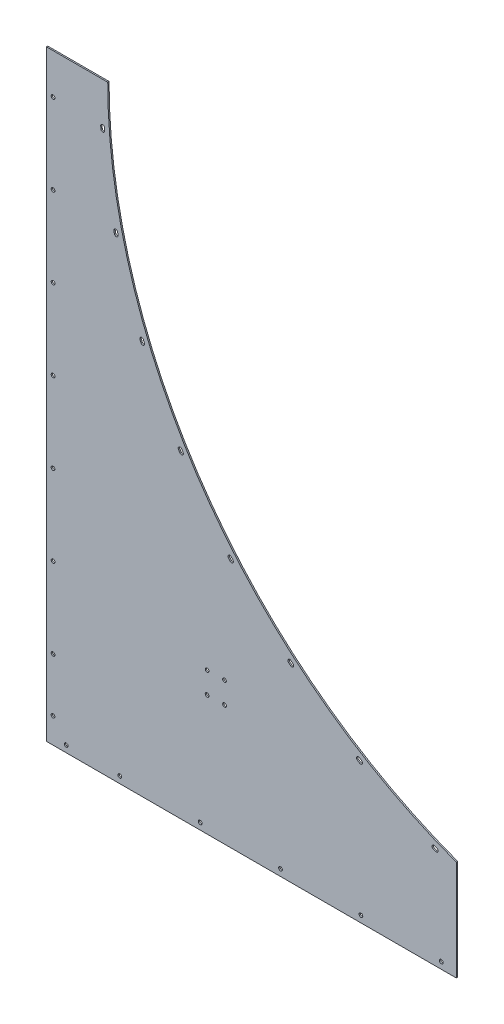
SolidWorks part; units mm, degrees
ref_plane "Front Plane" through (0, 0, 0) normal (0, 0, 1) x (1, 0, 0)
ref_plane "Top Plane" through (0, 0, 0) normal (0, 1, 0) x (1, 0, 0)
ref_plane "Right Plane" through (0, 0, 0) normal (1, 0, 0) x (0, 0, -1)
sketch "Sketch1" plane through (0, 0, 0) normal (0, 0, 1) x (1, 0, 0)
  line L0 (1502.6407, 642.1541) -> (1502.6407, 267.5522)
  line L1 (1502.6407, 267.5522) -> (-27.3593, 267.5522)
  line L2 (-27.3593, 267.5522) -> (-27.3593, 2512.5522)
  line L3 (-27.3593, 2512.5522) -> (201.6407, 2512.5522)
  line L4 (190.2384, 2349.6294) -> (189.4538, 2359.5986)
  line L5 (175.497, 2358.5002) -> (176.2816, 2348.531)
  line L6 (240.4273, 2037.7648) -> (238.0928, 2047.4885)
  line L7 (224.4796, 2044.2203) -> (226.8141, 2034.4966)
  line L8 (338.7846, 1737.591) -> (334.9578, 1746.8298)
  line L9 (322.0235, 1741.4723) -> (325.8503, 1732.2335)
  line L10 (482.8885, 1456.4994) -> (477.6636, 1465.0258)
  line L11 (465.7266, 1457.7108) -> (470.9516, 1449.1844)
  line L12 (669.1907, 1201.4112) -> (662.6962, 1209.0153)
  line L13 (652.0506, 1199.923) -> (658.545, 1192.3189)
  line L14 (893.1038, 978.6077) -> (885.4997, 985.1022)
  line L15 (876.4075, 974.4565) -> (884.0115, 967.962)
  line L16 (1149.1143, 793.575) -> (1140.5879, 798.8)
  line L17 (1133.2729, 786.863) -> (1141.7993, 781.6381)
  line L18 (1430.9183, 650.8693) -> (1421.6795, 654.6961)
  line L19 (1416.322, 641.7618) -> (1425.5608, 637.9349)
  arc A0 (201.6407, 2512.5522) -> (1502.6407, 642.1541) centre (2196.6407, 2512.5522) ccw
  circle A1 centre (1446.6407, 292.5522) radius 7
  circle A2 centre (1146.6407, 292.5522) radius 7
  circle A3 centre (846.6407, 292.5522) radius 7
  circle A4 centre (546.6407, 292.5522) radius 7
  circle A5 centre (246.6407, 292.5522) radius 7
  circle A6 centre (46.6407, 292.5522) radius 7
  circle A7 centre (-2.3593, 362.5522) radius 7
  circle A8 centre (-2.3593, 562.5522) radius 7
  circle A9 centre (-2.3593, 862.5522) radius 7
  circle A10 centre (-2.3593, 1162.5522) radius 7
  circle A11 centre (-2.3593, 1462.5522) radius 7
  circle A12 centre (-2.3593, 1762.5522) radius 7
  circle A13 centre (-2.3593, 2062.5522) radius 7
  circle A14 centre (-2.3593, 2362.5522) radius 7
  arc A15 (189.4538, 2359.5986) -> (175.497, 2358.5002) centre (182.4754, 2359.0494) ccw
  arc A16 (176.2816, 2348.531) -> (190.2384, 2349.6294) centre (183.26, 2349.0802) ccw
  arc A17 (238.0928, 2047.4885) -> (224.4796, 2044.2203) centre (231.2862, 2045.8544) ccw
  arc A18 (226.8141, 2034.4966) -> (240.4273, 2037.7648) centre (233.6207, 2036.1307) ccw
  arc A19 (334.9578, 1746.8298) -> (322.0235, 1741.4723) centre (328.4906, 1744.151) ccw
  arc A20 (325.8503, 1732.2335) -> (338.7846, 1737.591) centre (332.3175, 1734.9122) ccw
  arc A21 (477.6636, 1465.0258) -> (465.7266, 1457.7108) centre (471.6951, 1461.3683) ccw
  arc A22 (470.9516, 1449.1844) -> (482.8885, 1456.4994) centre (476.9201, 1452.8419) ccw
  arc A23 (662.6962, 1209.0153) -> (652.0506, 1199.923) centre (657.3734, 1204.4691) ccw
  arc A24 (658.545, 1192.3189) -> (669.1907, 1201.4112) centre (663.8679, 1196.8651) ccw
  arc A25 (885.4997, 985.1022) -> (876.4075, 974.4565) centre (880.9536, 979.7794) ccw
  arc A26 (884.0115, 967.962) -> (893.1038, 978.6077) centre (888.5577, 973.2849) ccw
  arc A27 (1140.5879, 798.8) -> (1133.2729, 786.863) centre (1136.9304, 792.8315) ccw
  arc A28 (1141.7993, 781.6381) -> (1149.1143, 793.575) centre (1145.4568, 787.6065) ccw
  arc A29 (1421.6795, 654.6961) -> (1416.322, 641.7618) centre (1419.0008, 648.2289) ccw
  arc A30 (1425.5608, 637.9349) -> (1430.9183, 650.8693) centre (1428.2396, 644.4021) ccw
  circle A31 centre (572.6407, 717.5522) radius 7
  circle A32 centre (637.6407, 717.5522) radius 7
  circle A33 centre (572.6407, 797.5522) radius 7
  circle A34 centre (637.6407, 797.5522) radius 7
extrude "Boss-Extrude1" add sketch "Sketch1" along normal blind 5
